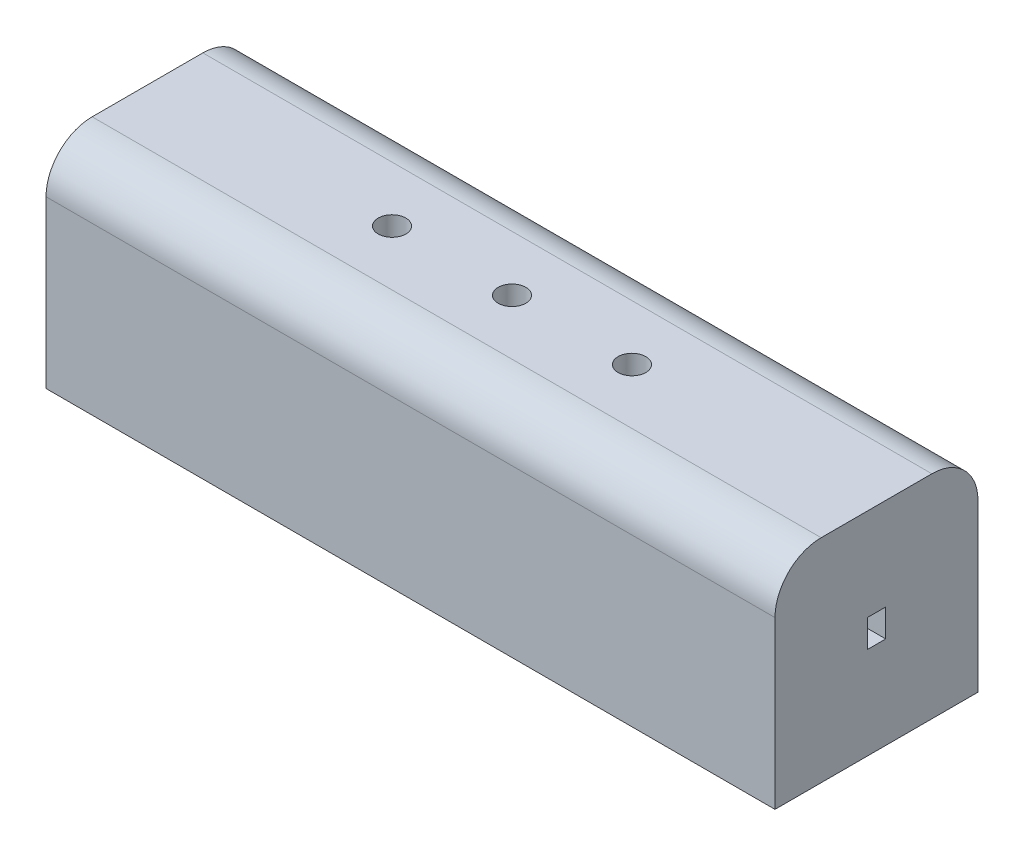
SolidWorks part; units mm, degrees
ref_plane "Plano frontal" through (0, 0, 0) normal (0, 0, 1) x (1, 0, 0)
ref_plane "Plano superior" through (0, 0, 0) normal (0, 1, 0) x (1, 0, 0)
ref_plane "Plano direito" through (0, 0, 0) normal (1, 0, 0) x (0, 0, -1)
sketch "Esboço1" plane through (0, 0, 0) normal (0, 1, 0) x (1, 0, 0)
  line L1 (-39.5, -11) -> (39.5, -11)
  line L2 (-39.5, -11) -> (-39.5, 11)
  line L3 (-39.5, 11) -> (39.5, 11)
  line L4 (39.5, -11) -> (39.5, 11)
  line L5 (-39.5, -11) -> (39.5, 11) construction
  line L6 (-39.5, 11) -> (39.5, -11) construction
  circle A0 centre (0, 0) radius 1.5
  circle A1 centre (-13, 0) radius 1.5
  circle A3 centre (13, 0) radius 1.5
  point P0 (0, 0)
sketch "Esboço2" plane through (0, 0, 0) normal (1, 0, 0) x (0, 0, -1)
  line L0 (-11, 0) -> (11, 0)
  line L1 (0, 23) -> (-6, 23)
  line L2 (0, 23) -> (6, 23)
  line L3 (-11, 18) -> (-11, 0)
  line L4 (-11, 0) -> (11, 0) construction
  line L5 (-11, 0) -> (11, 0) construction
  line L6 (11, 18) -> (11, 0)
  line L7 (11, 0) -> (-11, 0) construction
  arc A0 (-11, 18) -> (-6, 23) centre (-6, 18) cw
  arc A1 (11, 18) -> (6, 23) centre (6, 18) ccw
  dimension "D1" = 5
  dimension "D2" = 5
extrude "Extrusão-Fina1" add sketch "Esboço2" along normal up to vertex (39.5 mm away) and the other way up to vertex (39.5 mm away) thin contours L6 A1 L2 L1 A0 L3 L0
extrude "Corte-extrusão3" cut sketch "Esboço1" against normal through all and the other way through all contours A3 | A0 | A1
